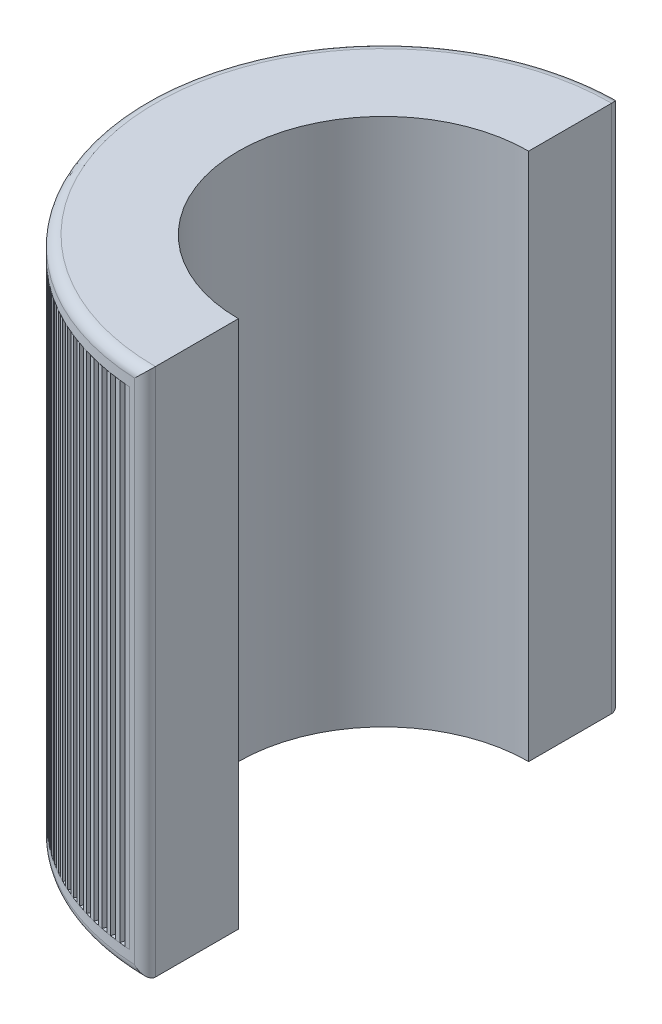
SolidWorks part; units mm, degrees
ref_plane "Ön Düzlem" through (0, 0, 0) normal (0, 0, 1) x (1, 0, 0)
ref_plane "Üst Düzlem" through (0, 0, 0) normal (0, 1, 0) x (1, 0, 0)
ref_plane "Sağ Düzlem" through (0, 0, 0) normal (1, 0, 0) x (0, 0, -1)
sketch "Çizim2" plane through (0, 0, 0) normal (0, 1, 0) x (1, 0, 0)
  line L0 (0, 115) -> (0, 70)
  line L1 (0, -70) -> (0, -115)
  arc A0 (0, 70) -> (0, -70) centre (0, 0) ccw
  arc A1 (0, 115) -> (0, -115) centre (0, 0) ccw
  dimension "D1" = 140
  dimension "D2" = 230
extrude "Yükseklik-Ekstrüzyon1" add sketch "Çizim2" along normal blind 255
shell "İç Boşaltma1" thickness 10
sketch "Çizim3" plane through (0, 10, 0) normal (0, 1, 0) x (1, 0, 0)
  line L0 (-10, 114.5644) -> (-10, 110.5338)
  line L1 (-10, 79.3725) -> (-10, 114.5644) construction
  line L2 (-10, 79.3725) -> (-10, 110.5338)
  line L3 (-12.2411, 114.3466) -> (-12.2411, 79.0579)
  arc A0 (-10, 114.5644) -> (-10, -114.5644) centre (0, 0) ccw construction
  arc A1 (-10, 114.5644) -> (-12.2411, 114.3466) centre (0, 0) ccw
  arc A2 (-10, 79.3725) -> (-10, -79.3725) centre (0, 0) ccw construction
  arc A3 (-10, 79.3725) -> (-12.2411, 79.0579) centre (0, 0) ccw
extrude "Yükseklik-Ekstrüzyon2" add sketch "Çizim3" along normal up to surface (235 mm away) separate body up to face at (-53.75, 245, 0)
pattern_circular "Dairesel Kaplama2" count 67 every 2.576 about axis through (0, 0, 0) along (0, 1, 0)
fillet "Radyus1" radius 5 4 edges at (0, 127.5, 115) (-115, 0, 0) (0, 127.5, -115) (-115, 255, 0)
